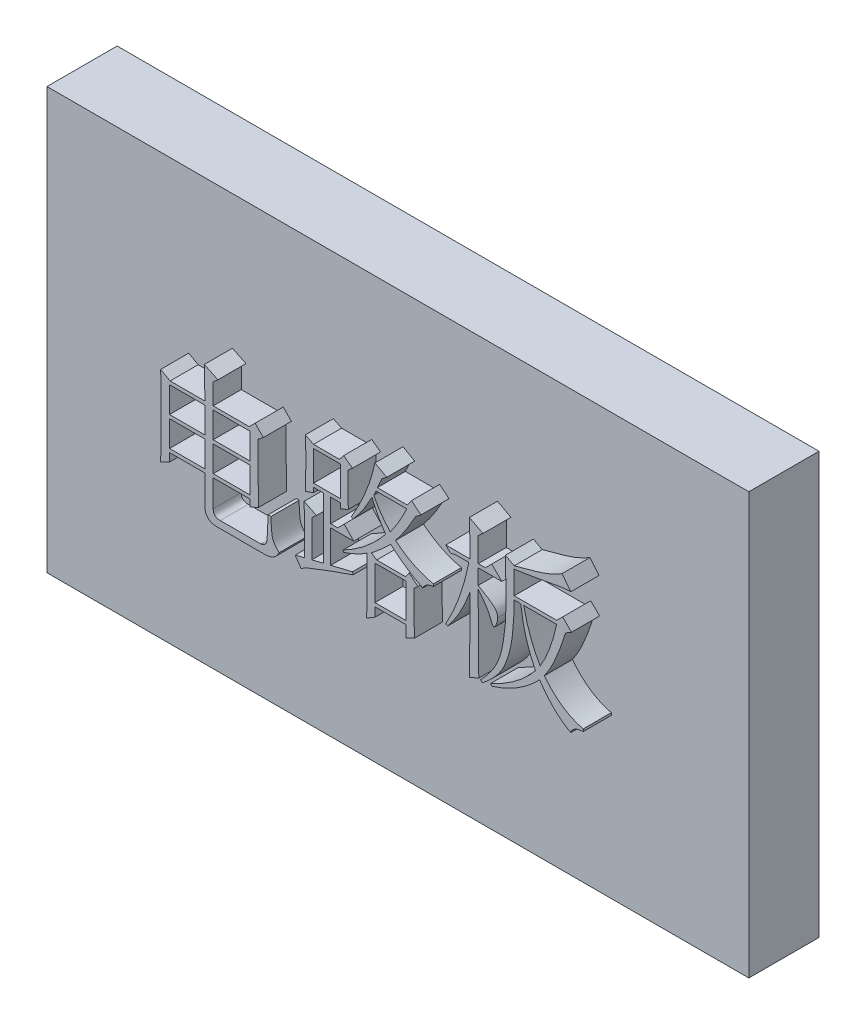
SolidWorks part; units mm, degrees
ref_plane "前视基准面" through (0, 0, 0) normal (0, 0, 1) x (1, 0, 0)
ref_plane "上视基准面" through (0, 0, 0) normal (0, 1, 0) x (1, 0, 0)
ref_plane "右视基准面" through (0, 0, 0) normal (1, 0, 0) x (0, 0, -1)
sketch "草图1" plane through (0, 0, 0) normal (0, 0, 1) x (1, 0, 0)
  line L1 (-12.5, 7.5) -> (12.5, 7.5)
  line L2 (-12.5, 7.5) -> (-12.5, -7.5)
  line L3 (-12.5, -7.5) -> (12.5, -7.5)
  line L4 (12.5, 7.5) -> (12.5, -7.5)
  line L5 (0, -7.5) -> (0, 7.5) construction
  line L6 (-12.5, 0) -> (12.5, 0) construction
  point P0 (0, 0)
  dimension "D1" = 15
  dimension "D2" = 25
extrude "凸台-拉伸1" add sketch "草图1" along normal blind 2.5
sketch "草图2" plane through (0, 0, 2.5) normal (0, 0, 1) x (1, 0, 0)
  text T0 "电路板"
extrude "凸台-拉伸3" add sketch "草图2" along normal blind 1
